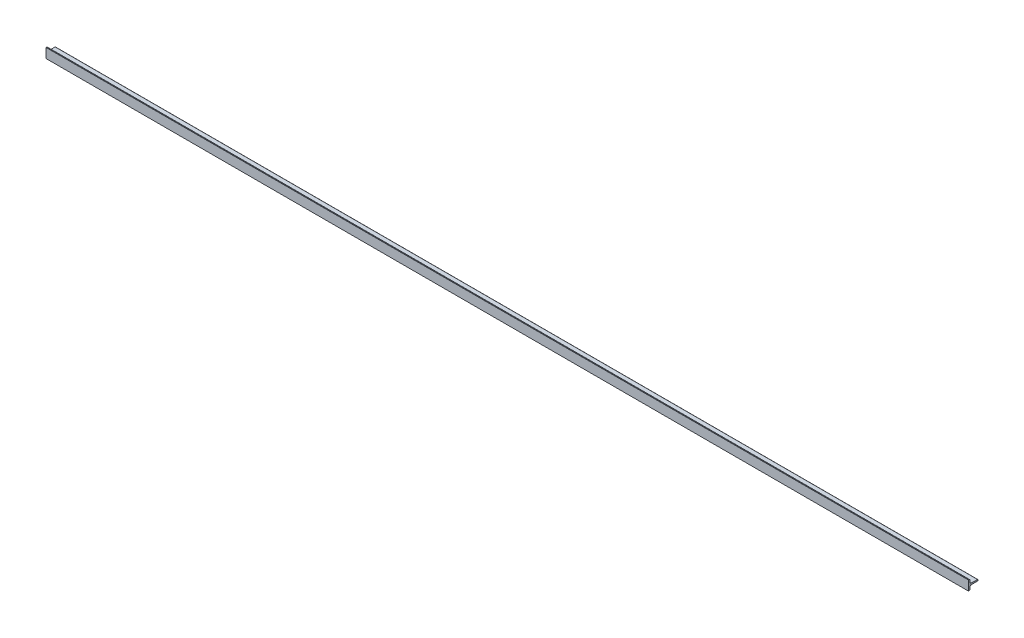
SolidWorks part; units mm, degrees
ref_plane "Front Plane" through (0, 0, 0) normal (0, 0, 1) x (1, 0, 0)
ref_plane "Top Plane" through (0, 0, 0) normal (0, 1, 0) x (1, 0, 0)
ref_plane "Right Plane" through (0, 0, 0) normal (1, 0, 0) x (0, 0, -1)
sketch "Sketch1" plane through (0, 0, 0) normal (0, 0, 1) x (1, 0, 0)
  line L0 (0, 0) -> (1920, 0)
  point P4 (0, 0)
  dimension "D1" = 1920
other "T section T 20 X 20(1)"
ref_plane "Plane1" through (0, 0, 0) normal (1, 0, 0) x (0, 1, 0)
sketch "Sketch12" plane through (0, 0, 0) normal (1, 0, 0) x (0, 1, 0)
  line L0 (-10, 20) -> (10, 20)
  line L2 (-1.3196, 0.98) -> (-1.581, 14.051)
  line L3 (-4.5204, 16.9904) -> (-8.53, 17.0706)
  line L5 (-10, 20) -> (-10, 18.5703)
  line L6 (10, 20) -> (10, 18.5703)
  line L7 (8.53, 17.0706) -> (4.5204, 16.9904)
  line L8 (1.581, 14.051) -> (1.3196, 0.98)
  line L9 (-5, 17) -> (5, 17) construction
  line L10 (0, 20) -> (0, 0) construction
  line L12 (-0.3198, 0) -> (0.3198, 0)
  arc A0 (-8.53, 17.0706) -> (-10, 18.5703) centre (-8.5, 18.5703) cw
  arc A1 (8.53, 17.0706) -> (10, 18.5703) centre (8.5, 18.5703) ccw
  arc A2 (-1.581, 14.051) -> (-4.5204, 16.9904) centre (-4.5804, 13.991) ccw
  arc A3 (4.5204, 16.9904) -> (1.581, 14.051) centre (4.5804, 13.991) ccw
  arc A4 (-0.3198, 0) -> (-1.3196, 0.98) centre (-0.3198, 1) cw
  arc A5 (1.3196, 0.98) -> (0.3198, 0) centre (0.3198, 1) cw
  point P16 (10, 17.1)
  point P24 (-1.3, 0)
  point P27 (1.3, 0)
  point P28 (0, 0)
  dimension "D2" = 1.146
  dimension "R2" = 1.5
  dimension "R1" = 3
  dimension "R3" = 1
  dimension "D1" = 1.146
  dimension "D3" = 2.9
  dimension "BF" = 20
  dimension "DEPTH" = 20
  dimension "TF" = 3
  dimension "D4" = 2.5999
  dimension "D5" = 1.146
